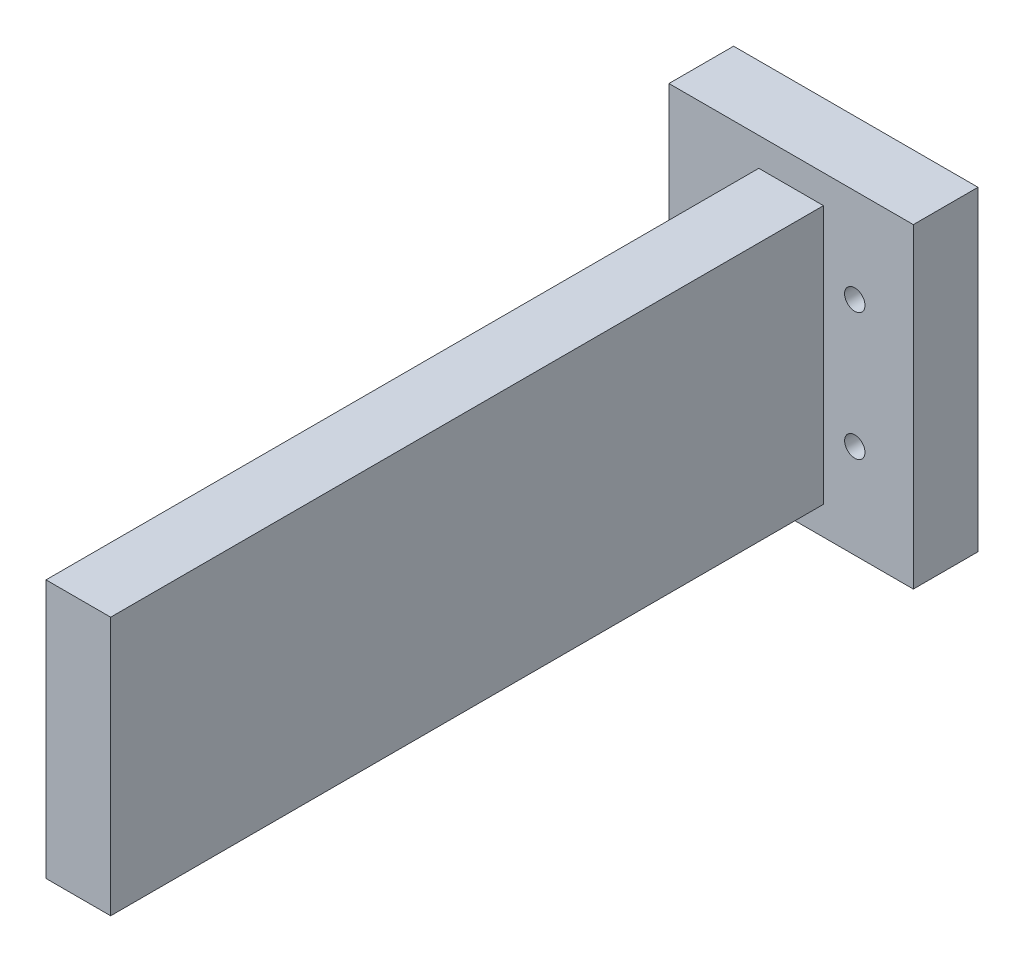
SolidWorks part; units mm, degrees
material "Aleación 1060"
ref_plane "Alzado" through (0, 0, 0) normal (0, 0, 1) x (1, 0, 0)
ref_plane "Planta" through (0, 0, 0) normal (0, 1, 0) x (1, 0, 0)
ref_plane "Vista lateral" through (0, 0, 0) normal (1, 0, 0) x (0, 0, -1)
sketch "Croquis1" plane through (0, 0, 0) normal (0, 0, 1) x (1, 0, 0)
  line L1 (24, -31) -> (-24, -31)
  line L2 (24, -31) -> (24, 31)
  line L3 (24, 31) -> (-24, 31)
  line L4 (-24, -31) -> (-24, 31)
  line L5 (24, -31) -> (-24, 31) construction
  line L6 (24, 31) -> (-24, -31) construction
  line L7 (12.5, -12.5) -> (-12.5, -12.5) construction
  line L8 (12.5, -12.5) -> (12.5, 12.5) construction
  line L9 (12.5, 12.5) -> (-12.5, 12.5) construction
  line L10 (-12.5, -12.5) -> (-12.5, 12.5) construction
  line L11 (12.5, -12.5) -> (-12.5, 12.5) construction
  line L12 (12.5, 12.5) -> (-12.5, -12.5) construction
  circle A0 centre (-12.5, 12.5) radius 1.997
  circle A1 centre (12.5, 12.5) radius 2.003
  circle A2 centre (-12.5, -12.5) radius 2.0101
  circle A3 centre (12.5, -12.5) radius 1.9951
  point P0 (0, 0)
  point P6 (0, 0)
  dimension "D1" = 62
  dimension "D2" = 48
  dimension "D3" = 25
  dimension "D4" = 25
extrude "Saliente-Extruir1" add sketch "Croquis1" along normal blind 12.7
sketch "Croquis2" plane through (0, 0, 12.7) normal (0, 0, 1) x (1, 0, 0)
  line L1 (6.35, -25.4) -> (-6.35, -25.4)
  line L2 (6.35, -25.4) -> (6.35, 25.4)
  line L3 (6.35, 25.4) -> (-6.35, 25.4)
  line L4 (-6.35, -25.4) -> (-6.35, 25.4)
  line L5 (6.35, -25.4) -> (-6.35, 25.4) construction
  line L6 (6.35, 25.4) -> (-6.35, -25.4) construction
  point P0 (0, 0)
  dimension "D1" = 50.8
  dimension "D2" = 12.7
extrude "Saliente-Extruir2" add sketch "Croquis2" along normal blind 140
